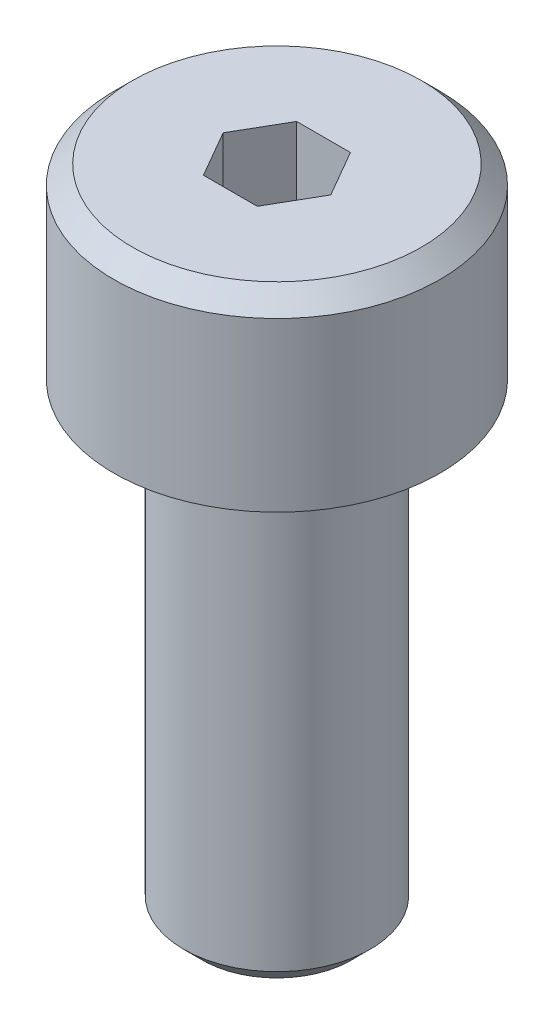
SolidWorks part; units mm, degrees
ref_plane "Front Plane" through (0, 0, 0) normal (0, 0, 1) x (1, 0, 0)
ref_plane "Top Plane" through (0, 0, 0) normal (0, 1, 0) x (1, 0, 0)
ref_plane "Right Plane" through (0, 0, 0) normal (1, 0, 0) x (0, 0, -1)
sketch "Sketch2" plane through (0, 0, 0) normal (0, 0, 1) x (1, 0, 0)
  line L0 (0, 0) -> (0, 25) construction
  line L1 (0, 14) -> (3.5, 14)
  line L2 (3.5, 14) -> (3.5, 10)
  line L3 (3.5, 10) -> (2, 10)
  line L4 (2, 10) -> (2, 0)
  line L5 (2, 0) -> (0, 0)
  line L6 (0, 0) -> (0, 14)
  dimension "D1" = 4
  dimension "D2" = 7
  dimension "D3" = 4
  dimension "D4" = 14
revolve "Revolve1" add sketch "Sketch2" angle 360 about L0
chamfer "Chamfer1" distance 0.4 angle 45 2 edges at (0, 14, -3.5) (0, 0, -2)
sketch "Sketch4" plane through (0, 14, 0) normal (0, 1, 0) x (1, 0, 0)
  line L1 (1.1547, 0) -> (0.5774, 1)
  line L2 (0.5774, 1) -> (-0.5774, 1)
  line L3 (-0.5774, 1) -> (-1.1547, 0)
  line L4 (-1.1547, 0) -> (-0.5774, -1)
  line L5 (-0.5774, -1) -> (0.5774, -1)
  line L6 (0.5774, -1) -> (1.1547, 0)
  circle A0 centre (0, 0) radius 1 construction
  dimension "D1" = 2
extrude "Cut-Extrude2" cut sketch "Sketch4" against normal blind 4
